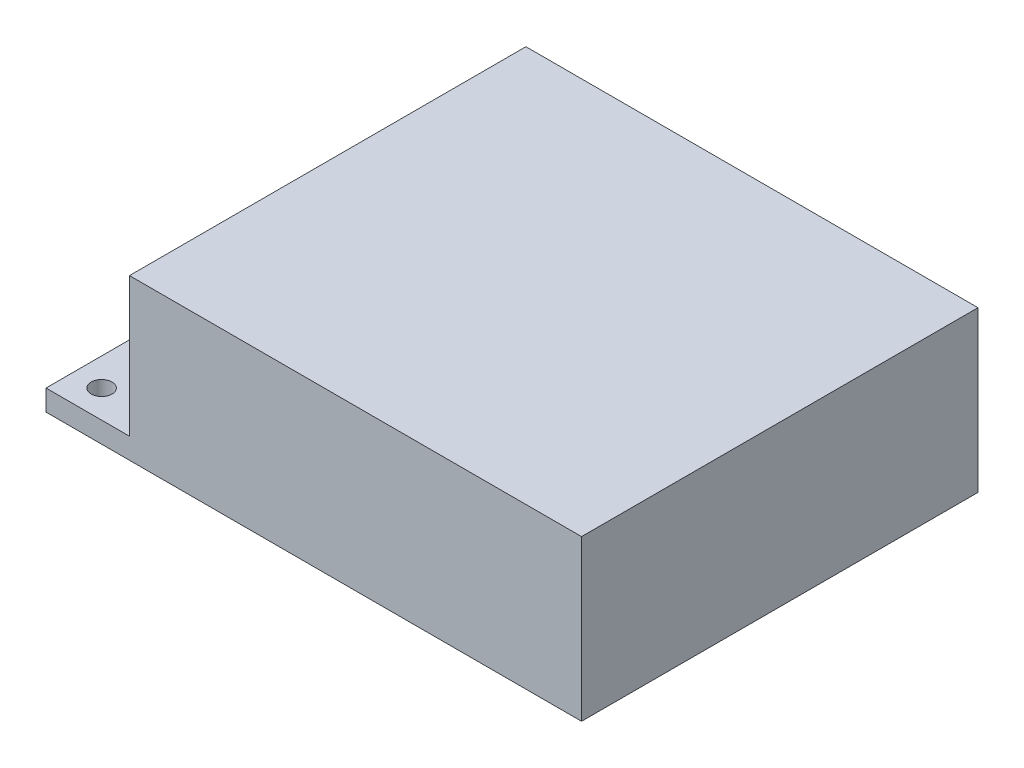
SolidWorks part; units mm, degrees
ref_plane "Front Plane" through (0, 0, 0) normal (0, 0, 1) x (1, 0, 0)
ref_plane "Top Plane" through (0, 0, 0) normal (0, 1, 0) x (1, 0, 0)
ref_plane "Right Plane" through (0, 0, 0) normal (1, 0, 0) x (0, 0, -1)
sketch "Sketch1" plane through (0, 0, 0) normal (0, 1, 0) x (1, 0, 0)
  line L0 (-38.5, 0) -> (38.5, 0) construction
  line L1 (-38.5, -28.5) -> (38.5, -28.5)
  line L2 (-38.5, -28.5) -> (-38.5, 28.5)
  line L3 (-38.5, 28.5) -> (38.5, 28.5)
  line L4 (38.5, -28.5) -> (38.5, 28.5)
  line L5 (-38.5, -28.5) -> (38.5, 28.5) construction
  line L6 (-38.5, 28.5) -> (38.5, -28.5) construction
  circle A0 centre (-34.5, 24.5) radius 1.5
  circle A1 centre (-34.5, -24.5) radius 1.5
  point P0 (0, 0)
  point P10 (-35.6176, -24.5)
  point P11 (-31.7025, 24.5)
  dimension "D3" = 3
  dimension "D1" = 57
  dimension "D2" = 77
  dimension "D4" = 49
  dimension "D5" = 4
extrude "Boss-Extrude1" add sketch "Sketch1" along normal blind 3
sketch "Sketch2" plane through (0, 3, 0) normal (0, 1, 0) x (1, 0, 0)
  line L0 (-38.5, -28.5) -> (38.5, -28.5) construction
  line L1 (38.5, 28.5) -> (-26.5, 28.5)
  line L2 (38.5, 28.5) -> (38.5, -28.5)
  line L3 (38.5, -28.5) -> (-26.5, -28.5)
  line L4 (-26.5, 28.5) -> (-26.5, -28.5)
  dimension "D1" = 65
extrude "Boss-Extrude2" add sketch "Sketch2" along normal blind 20
